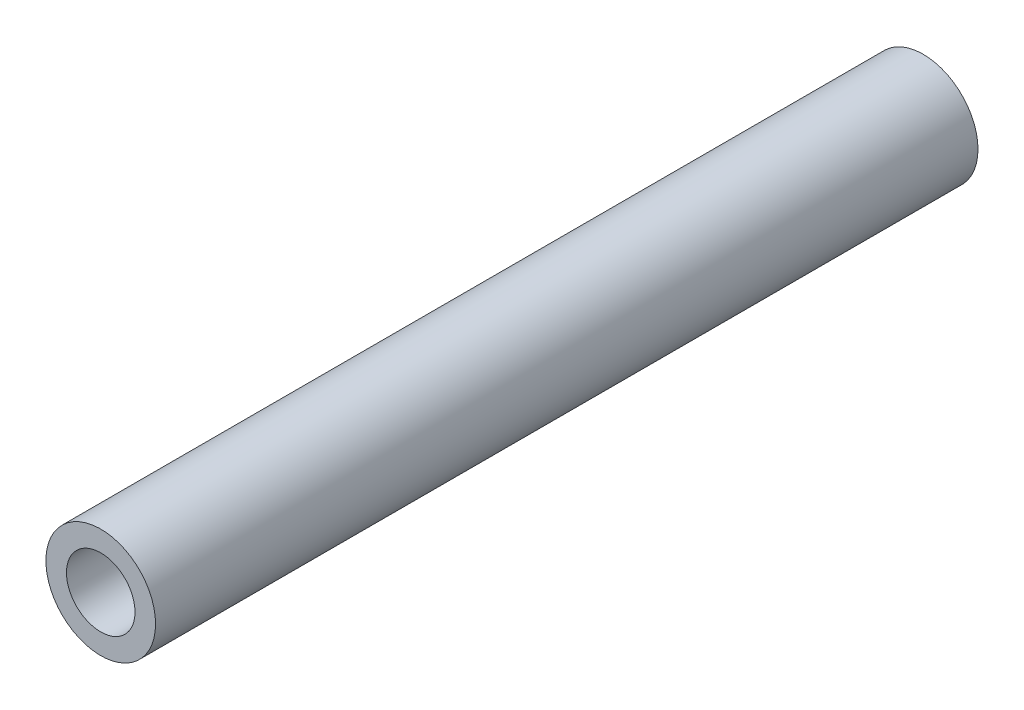
SolidWorks part; units mm, degrees
material "6061 Alloy"
ref_plane "Front Plane" through (0, 0, 0) normal (0, 0, 1) x (1, 0, 0)
ref_plane "Top Plane" through (0, 0, 0) normal (0, 1, 0) x (1, 0, 0)
ref_plane "Right Plane" through (0, 0, 0) normal (1, 0, 0) x (0, 0, -1)
sketch "Sketch1" plane through (0, 0, 0) normal (0, 0, 1) x (1, 0, 0)
  circle A0 centre (0, 0) radius 4
  circle A1 centre (0, 0) radius 2.5
  dimension "D1" = 5
  dimension "D2" = 8
extrude "Boss-Extrude1" add sketch "Sketch1" along normal blind 60
